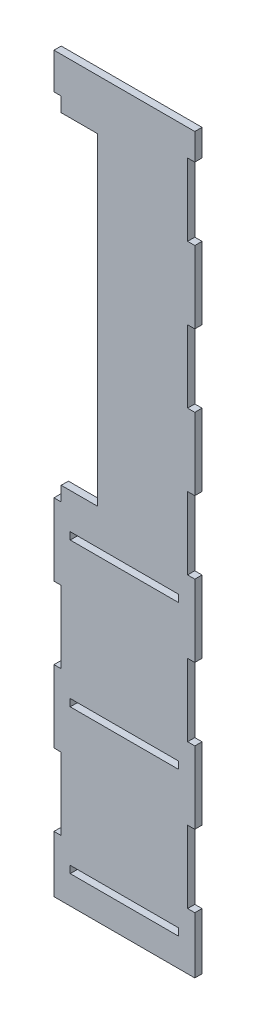
SolidWorks part; units mm, degrees
ref_plane "前视基准面" through (0, 0, 0) normal (0, 0, 1) x (1, 0, 0)
ref_plane "上视基准面" through (0, 0, 0) normal (0, 1, 0) x (1, 0, 0)
ref_plane "右视基准面" through (0, 0, 0) normal (1, 0, 0) x (0, 0, -1)
sketch "草图1" plane through (0, 0, 0) normal (0, 0, 1) x (1, 0, 0)
  line L91 (-8, 49) -> (-8, 45)
  line L93 (2, 33.8931) -> (2, -33.9722)
  line L96 (-8, -48.3425) -> (-10, -48.3425)
  line L97 (-10, -48.3425) -> (-10, -68.3425)
  line L98 (-10, -68.3425) -> (-8, -68.3425)
  line L99 (-8, -68.3425) -> (-8, -88.3425)
  line L100 (-8, -88.3425) -> (-10, -88.3425)
  line L101 (-10, -88.3425) -> (-10, -108.3425)
  line L102 (-10, -108.3425) -> (-8, -108.3425)
  line L105 (-8, -144) -> (27, -144)
  line L112 (27, -48.3425) -> (29, -48.3425)
  line L113 (29, -48.3425) -> (29, -68.3425)
  line L114 (29, -68.3425) -> (27, -68.3425)
  line L115 (27, -88.3425) -> (29, -88.3425)
  line L116 (29, -88.3425) -> (29, -108.3425)
  line L117 (29, -108.3425) -> (27, -108.3425)
  line L119 (27, -88.3425) -> (27, -68.3425)
  line L121 (9.5, -54.2215) -> (24.5, -54.2215)
  line L135 (9.5, -54.2215) -> (-5.5, -54.2215)
  line L136 (-5.5, -54.2215) -> (-5.5, -56.2215)
  line L143 (24.5, -54.2215) -> (24.5, -56.2215)
  line L144 (24.5, -56.2215) -> (-5.5, -56.2215)
  line L145 (27, -108.3425) -> (27, -128.3425)
  line L146 (24.5, -94.2215) -> (-5.5, -94.2215)
  line L147 (-5.5, -94.2215) -> (-5.5, -96.2215)
  line L148 (-5.5, -96.2215) -> (24.5, -96.2215)
  line L149 (24.5, -94.2215) -> (24.5, -96.2215)
  line L150 (24.5, -134.2215) -> (-5.5, -134.2215)
  line L151 (-5.5, -134.2215) -> (-5.5, -136.2215)
  line L152 (-5.5, -136.2215) -> (24.5, -136.2215)
  line L153 (24.5, -136.2215) -> (24.5, -134.2215)
  line L154 (27, -128.3425) -> (29, -128.3425)
  line L155 (29, -128.3425) -> (29, -144)
  line L156 (29, -144) -> (27, -144)
  line L157 (-8, -108.3425) -> (-8, -128.3425)
  line L158 (-8, -128.3425) -> (-10, -128.3425)
  line L159 (-10, -128.3425) -> (-10, -144)
  line L160 (-8, -144) -> (-10, -144)
  line L161 (27, -48.3425) -> (27, -28.3425)
  line L162 (27, -28.3425) -> (29, -28.3425)
  line L163 (29, -28.3425) -> (29, -8.3425)
  line L164 (29, -8.3425) -> (27, -8.3425)
  line L165 (27, -8.3425) -> (27, 11.6575)
  line L166 (27, 11.6575) -> (29, 11.6575)
  line L167 (29, 11.6575) -> (29, 31.6575)
  line L169 (27, 31.6575) -> (29, 31.6575)
  line L170 (-8, -48.3425) -> (-8, -44.3425)
  line L171 (-8, -44.3425) -> (2, -44.3425)
  line L172 (2, -44.3425) -> (2, -33.9722)
  line L173 (-8, 49) -> (-10, 49)
  line L174 (-10, 49) -> (-10, 59)
  line L175 (-10, 59) -> (29, 59)
  line L178 (29, 59) -> (29, 51.6575)
  line L179 (29, 51.6575) -> (27, 51.6575)
  line L180 (27, 51.6575) -> (27, 31.6575)
  line L181 (-8, 45) -> (2, 45)
  line L182 (2, 45) -> (2, 33.8931)
extrude "凸台-拉伸2" add sketch "草图1" along normal blind 2
